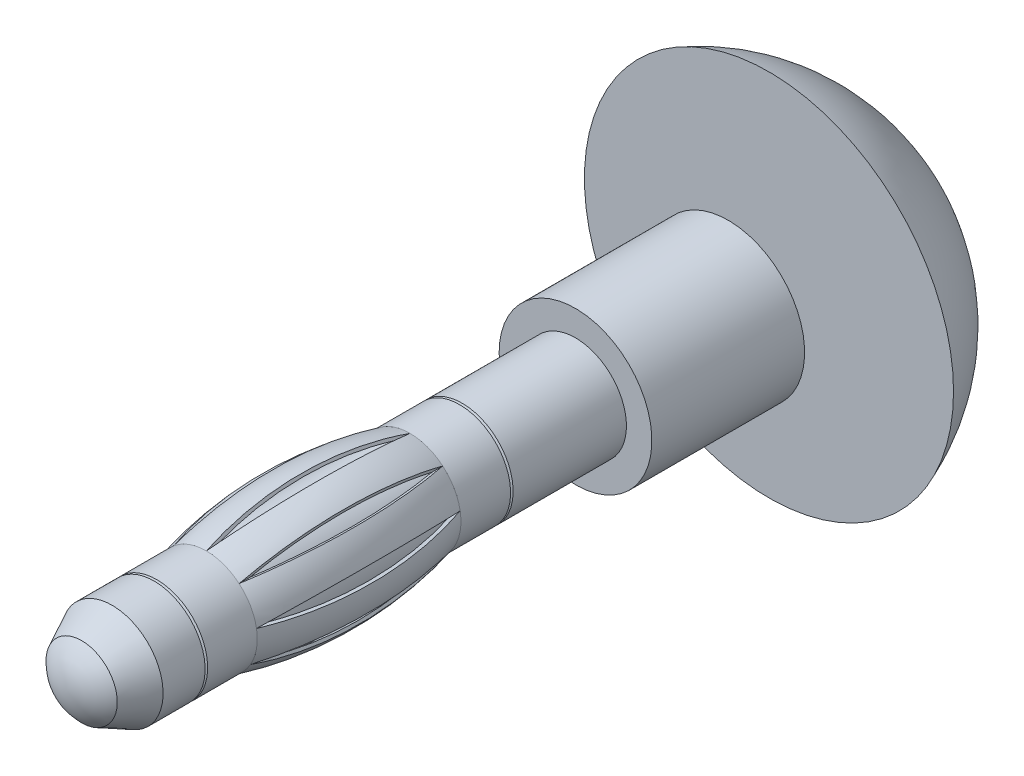
SolidWorks part; units mm, degrees
ref_plane "Plan de face" through (0, 0, 0) normal (0, 0, 1) x (1, 0, 0)
ref_plane "Plan de dessus" through (0, 0, 0) normal (0, 1, 0) x (1, 0, 0)
ref_plane "Plan de droite" through (0, 0, 0) normal (1, 0, 0) x (0, 0, -1)
sketch "Esquisse1" plane through (0, 0, 0) normal (1, 0, 0) x (0, 0, -1)
  line L0 (0, 0) -> (-22.0751, 0) construction
  line L1 (0, 1.55) -> (0, 3)
  line L2 (0, 3) -> (-6, 3)
  line L3 (-6, 3) -> (-6, 2)
  line L4 (-6, 2) -> (-10.45, 2)
  line L5 (-20.5, 2) -> (-22.45, 2)
  line L6 (-24.2, 2) -> (-25.4, 1.4)
  line L7 (-0.3, 1.25) -> (-6.7, 1.25)
  line L8 (-7, 0.95) -> (-7, 0)
  line L9 (-7, 0) -> (-26, 0)
  line L10 (-6.7, 1.25) -> (-7, 0.95)
  line L11 (0, 1.55) -> (-0.3, 1.25)
  line L13 (-12.9279, 2) -> (-12.9279, 1.9)
  line L14 (-12.9279, 1.9) -> (-20.0721, 1.9)
  line L15 (-20.0721, 1.9) -> (-20.0721, 2)
  line L16 (-16.5, 2.5) -> (-16.5, 0) construction
  line L17 (-22.55, 2) -> (-22.5, 1.9)
  line L18 (-22.5, 1.9) -> (-22.45, 2)
  line L19 (-22.5, 1.9) -> (-22.5, 2) construction
  line L21 (-10.5, 1.9) -> (-10.55, 2)
  line L22 (-10.45, 2) -> (-10.5, 1.9)
  line L23 (-10.55, 2) -> (-12.5, 2)
  line L25 (-22.55, 2) -> (-24.2, 2)
  arc A0 (-12.5, 2) -> (-20.5, 2) centre (-16.5, -13.75) ccw
  arc A2 (-25.4, 1.4) -> (-26, 0) centre (-24.0667, 0) ccw
  arc A3 (-20.0721, 2) -> (-12.9279, 2) centre (-16.5, -13.75) cw
  point P3 (0, 1.25)
  point P14 (-8.8964, -1.1669)
  point P16 (-16.5, 2.5)
  point P17 (-7, 1.25)
  dimension "D1" = 2.5
  dimension "D13" = 0.1
  dimension "D2" = 6
  dimension "D3" = 4
  dimension "D4" = 7
  dimension "D5" = 8
  dimension "D6" = 6
  dimension "D7" = 5
  dimension "D8" = 5.5
  dimension "D9" = 1.8
  dimension "D10" = 2.8
  dimension "D11" = 26
  dimension "D12" = 0.6
  dimension "D14" = 0.1
  dimension "D15" = 12
  dimension "D18" = 0.1
  dimension "D19" = 0.1
revolve "base" add sketch "Esquisse1" angle 360 about L0
sketch "Esquisse2" plane through (0, 0, 0) normal (0, 0, 1) x (1, 0, 0)
  line L0 (0, 0) -> (0, 3) construction
  line L1 (0.3, 2.5) -> (-0.3, 2.5)
  line L2 (-0.3, 2.5) -> (0, 2)
  line L3 (0.3, 2.5) -> (0, 2)
  line L4 (1.8368, 1.7223) -> (1.2856, 1.5321)
  line L5 (1.3772, 2.1079) -> (1.2856, 1.5321)
  line L6 (1.8368, 1.7223) -> (1.3772, 2.1079)
  line L7 (2.5141, 0.1387) -> (1.9696, 0.3473)
  line L8 (2.4099, 0.7296) -> (1.9696, 0.3473)
  line L9 (2.5141, 0.1387) -> (2.4099, 0.7296)
  line L10 (2.0151, -1.5098) -> (1.7321, -1)
  line L11 (2.3151, -0.9902) -> (1.7321, -1)
  line L12 (2.0151, -1.5098) -> (2.3151, -0.9902)
  line L13 (0.5731, -2.4518) -> (0.684, -1.8794)
  line L14 (1.137, -2.2466) -> (0.684, -1.8794)
  line L15 (0.5731, -2.4518) -> (1.137, -2.2466)
  line L16 (-1.137, -2.2466) -> (-0.684, -1.8794)
  line L17 (-0.5731, -2.4518) -> (-0.684, -1.8794)
  line L18 (-1.137, -2.2466) -> (-0.5731, -2.4518)
  line L19 (-2.3151, -0.9902) -> (-1.7321, -1)
  line L20 (-2.0151, -1.5098) -> (-1.7321, -1)
  line L21 (-2.3151, -0.9902) -> (-2.0151, -1.5098)
  line L22 (-2.4099, 0.7296) -> (-1.9696, 0.3473)
  line L23 (-2.5141, 0.1387) -> (-1.9696, 0.3473)
  line L24 (-2.4099, 0.7296) -> (-2.5141, 0.1387)
  line L25 (-1.3772, 2.1079) -> (-1.2856, 1.5321)
  line L26 (-1.8368, 1.7223) -> (-1.2856, 1.5321)
  line L27 (-1.3772, 2.1079) -> (-1.8368, 1.7223)
  circle A0 centre (0, 0) radius 3 construction
  circle A3 centre (0, 0) radius 2.5 construction
  circle A4 centre (0, 0) radius 2 construction
  circle A5 centre (0, 0) radius 2 construction
  point P14 (0, 2.5)
  point P40 (0, 0)
  dimension "D1" = 0.6
  dimension "D2" = 9
extrude "Enlèv. mat.-Extru.2" cut sketch "Esquisse2" along normal through all from offset 6
sketch "Esquisse3" plane through (0, 0, 0) normal (0, 1, 0) x (1, 0, 0)
  line L0 (0, 0) -> (0, 6.6) construction
  line L1 (7.25, 1.6) -> (0, 1.6)
  line L2 (0, 6.6) -> (0, 1.6)
  arc A0 (0, 6.6) -> (7.25, 1.6) centre (0, -1.1562) cw
  dimension "D1" = 1.6
  dimension "D2" = 14.5
  dimension "D3" = 5
revolve "Révolution1" add sketch "Esquisse3" angle 360 about L0
